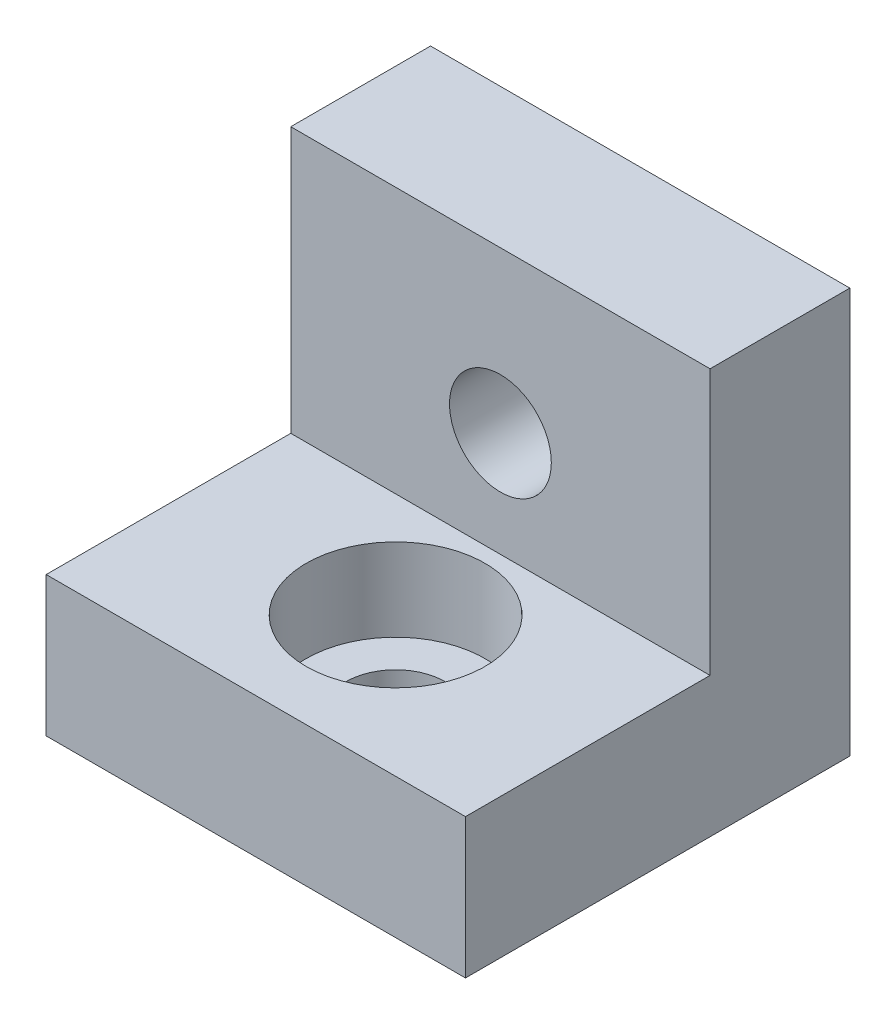
SolidWorks part; units mm, degrees
ref_plane "Front Plane" through (0, 0, 0) normal (0, 0, 1) x (1, 0, 0)
ref_plane "Top Plane" through (0, 0, 0) normal (0, 1, 0) x (1, 0, 0)
ref_plane "Right Plane" through (0, 0, 0) normal (1, 0, 0) x (0, 0, -1)
sketch "Sketch1" plane through (0, 0, 0) normal (0, 1, 0) x (1, 0, 0)
  line L1 (-6.858, 10.795) -> (8.382, 10.795)
  line L2 (-6.858, 10.795) -> (-6.858, -3.175)
  line L3 (-6.858, -3.175) -> (8.382, -3.175)
  line L4 (8.382, 10.795) -> (8.382, -3.175)
  dimension "D1" = 15.24
  dimension "D2" = 13.97
  dimension "D3" = 8.382
  dimension "D4" = 10.795
extrude "Boss-Extrude1" add sketch "Sketch1" along normal blind 5.08
sketch "Sketch2" plane through (0, 5.08, 0) normal (0, 1, 0) x (1, 0, 0)
  line L0 (8.382, -3.175) -> (8.382, 10.795) construction
  line L1 (-6.858, 10.795) -> (8.382, 10.795)
  line L2 (-6.858, 10.795) -> (-6.858, 5.715)
  line L3 (-6.858, 5.715) -> (8.382, 5.715)
  line L4 (8.382, 10.795) -> (8.382, 5.715)
  dimension "D1" = 5.08
extrude "Boss-Extrude2" add sketch "Sketch2" along normal blind 9.652
sketch "Sketch3" plane through (0, 0, -5.715) normal (0, 0, 1) x (1, 0, 0)
  line L1 (-6.858, 0) -> (8.382, 0) construction
  line L2 (8.382, 14.732) -> (8.382, 5.08) construction
  circle A0 centre (0.762, 8.89) radius 1.16
  dimension "D1" = 8.89
  dimension "D2" = 7.62
hole_wizard "M3 Clearance Hole1" positions "Sketch4" profile "Sketch5" hole size "M3" standard "ANSI Metric"
sketch "Sketch4" plane through (0, 0, -5.715) normal (0, 0, 1) x (1, 0, 0)
  point P0 (0.762, 8.89)
sketch "Sketch5" plane through (0.762, 8.89, -5.715) normal (1, 0, 0) x (0, -1, 0)
  line L0 (0, 0) -> (0, 26.5116)
  line L1 (0, 26.5116) -> (1.85, 25.4)
  line L2 (1.85, 25.4) -> (1.85, 0)
  line L5 (1.85, 0) -> (0, 0)
  line L10 (0, 26.5116) -> (-1.85, 25.4) construction
  line L11 (0, -6.35) -> (0, 107.95) construction
  dimension "Hole Dia." = 3.7
  dimension "Hole Depth" = 25.4
  dimension "Drill Angle" = 118
sketch "Sketch6" plane through (0, 5.08, 0) normal (0, 1, 0) x (1, 0, 0)
  line L0 (8.382, -3.175) -> (8.382, 5.715) construction
  line L1 (8.382, 10.795) -> (-6.858, 10.795) construction
  circle A0 centre (0.762, 1.905) radius 1.4589
  dimension "D1" = 7.62
  dimension "D2" = 8.89
hole_wizard "CBORE for M3 SHCS2" positions "Sketch7" profile "Sketch8" counterbore size "M3" standard "ANSI Metric"
sketch "Sketch7" plane through (0, 5.08, 0) normal (0, 1, 0) x (1, 0, 0)
  point P0 (0.762, 1.905)
sketch "Sketch8" plane through (0.762, 5.08, -1.905) normal (1, 0, 0) x (0, 0, 1)
  line L0 (0, 0) -> (0, 26.4815)
  line L1 (0, 26.4815) -> (1.8, 25.4)
  line L2 (1.8, 25.4) -> (1.8, 3)
  line L3 (1.8, 3) -> (3.25, 3)
  line L4 (3.25, 3) -> (3.25, 0)
  line L5 (3.25, 0) -> (0, 0)
  line L10 (0, 26.4815) -> (-1.8, 25.4) construction
  line L11 (0, -6.35) -> (0, 107.95) construction
  dimension "Hole Dia." = 3.6
  dimension "Hole Depth" = 25.4
  dimension "C'Bore Dia." = 6.5
  dimension "C'Bore Depth" = 3
  dimension "Drill Angle" = 118
